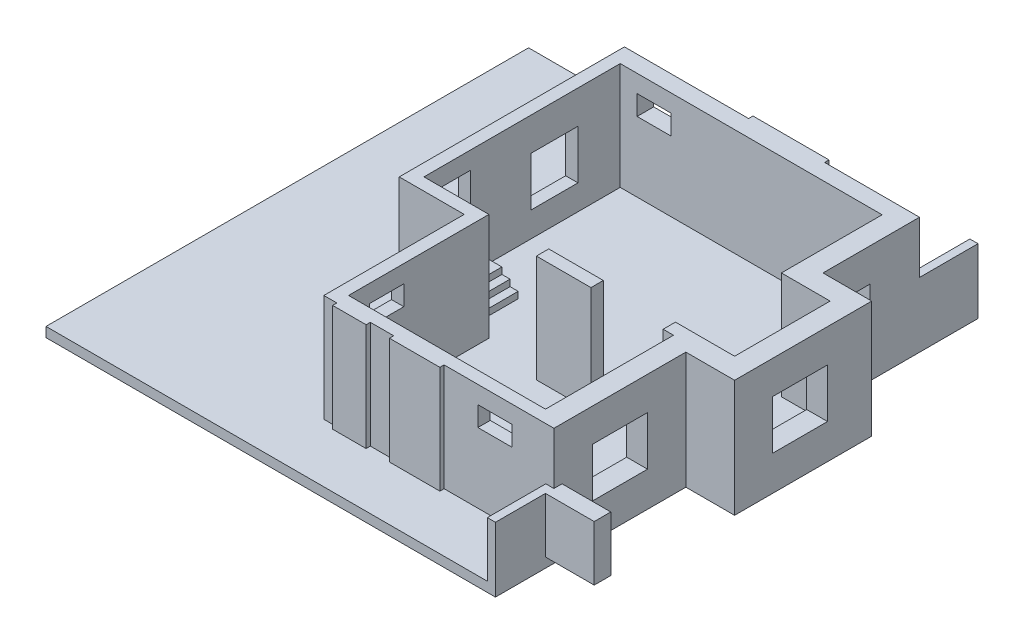
SolidWorks part; units mm, degrees
ref_plane "Спереди" through (0, 0, 0) normal (0, 0, 1) x (1, 0, 0)
ref_plane "Сверху" through (0, 0, 0) normal (0, 1, 0) x (1, 0, 0)
ref_plane "Справа" through (0, 0, 0) normal (1, 0, 0) x (0, 0, -1)
sketch "Эскиз2" plane through (0, 0, 0) normal (0, 1, 0) x (1, 0, 0)
  line L0 (0, 0) -> (-14310, 0) construction
  line L1 (0, 0) -> (0, -10805) construction
  line L2 (0, -3035) -> (-14310, -3035) construction
  line L3 (0, -6485) -> (-14310, -6485) construction
  line L4 (-1500, 0) -> (-1500, -10805) construction
  line L5 (-14310, 0) -> (-14310, -10805) construction
  line L6 (0, -10805) -> (-14310, -10805) construction
  dimension "D1" = 1500
  dimension "D2" = 12810
  dimension "D3" = 3035
  dimension "D4" = 3450
  dimension "D5" = 4320
sketch "Эскиз1" plane through (0, 0, 0) normal (0, 1, 0) x (1, 0, 0)
  line L0 (0, 0) -> (-14310, 0) construction
  line L1 (-1500, 0) -> (-1500, -10805) construction
  line L2 (0, -3035) -> (-14310, -3035) construction
  line L3 (0, 0) -> (0, -10805) construction
  line L4 (0, -6485) -> (-14310, -6485) construction
  line L5 (0, -10805) -> (-14310, -10805) construction
  line L6 (-7880, -6675) -> (-7880, -6295)
  line L7 (-10260, 255) -> (-6440, 255)
  line L8 (-6440, 255) -> (-6440, 390)
  line L9 (-6440, 390) -> (-4100, 390)
  line L10 (-4100, 390) -> (-4100, 255)
  line L11 (-4100, 255) -> (-1180, 255)
  line L12 (-1180, 255) -> (-1180, -2715)
  line L13 (-1180, -2715) -> (320, -2715)
  line L14 (320, -2715) -> (320, -6935)
  line L15 (320, -6935) -> (-1180, -6935)
  line L16 (-1180, -6935) -> (-1180, -10995)
  line L17 (-10260, 255) -> (-10260, -6675)
  line L18 (-10260, -6675) -> (-8260, -6675)
  line L19 (-8260, -6675) -> (-8260, -10995)
  line L20 (-1180, -10995) -> (-4560, -10995)
  line L21 (-4560, -10995) -> (-4560, -11125)
  line L22 (-4560, -11125) -> (-6110, -11125)
  line L23 (-6110, -11125) -> (-6110, -10995)
  line L24 (-6110, -10995) -> (-6830, -10995)
  line L25 (-6830, -10995) -> (-6830, -11125)
  line L26 (-6830, -11125) -> (-7860, -11125)
  line L27 (-7860, -11125) -> (-7860, -10995)
  line L28 (-7860, -10995) -> (-8260, -10995)
  line L29 (-9880, -255) -> (-1820, -255)
  line L30 (-1820, -255) -> (-1820, -3355)
  line L31 (-1820, -3355) -> (-320, -3355)
  line L32 (-320, -3355) -> (-320, -6295)
  line L33 (-320, -6295) -> (-2140, -6295)
  line L34 (-2140, -6295) -> (-2140, -6675)
  line L35 (-1820, -10615) -> (-7880, -10615)
  line L36 (-7880, -10615) -> (-7880, -6675)
  line L39 (-7880, -6295) -> (-9880, -6295)
  line L40 (-9880, -6295) -> (-9880, -255)
  line L41 (-2140, -6675) -> (-1820, -6675)
  line L42 (-6040, -6295) -> (-4360, -6295)
  line L43 (-6040, -6295) -> (-6040, -6675)
  line L44 (-6040, -6675) -> (-4360, -6675)
  line L45 (-4360, -6295) -> (-4360, -6675)
  line L46 (-1820, -6675) -> (-1820, -10615)
  dimension "D4" = 255
  dimension "D5" = 510
  dimension "D6" = 320
  dimension "D7" = 135
  dimension "D8" = 135
  dimension "D9" = 640
  dimension "D10" = 320
  dimension "D11" = 640
  dimension "D12" = 320
  dimension "D13" = 640
  dimension "D14" = 450
  dimension "D15" = 2340
  dimension "D16" = 3820
  dimension "D17" = 640
  dimension "D18" = 640
  dimension "D19" = 130
  dimension "D20" = 130
  dimension "D21" = 1550
  dimension "D22" = 720
  dimension "D23" = 1030
  dimension "D24" = 400
  dimension "D25" = 320
  dimension "D26" = 190
  dimension "D28" = 380
  dimension "D29" = 320
  dimension "D30" = 1680
  dimension "D31" = 2220
  dimension "D32" = 380
  dimension "D33" = 3380
  dimension "D34" = 190
  dimension "D35" = 9080
  dimension "D38" = 380
extrude "Бобышка-Вытянуть1" add sketch "Эскиз1" along normal blind 3300
sketch "Эскиз3" plane through (0, 0, 0) normal (0, 1, 0) x (1, 0, 0)
  line L0 (-1180, -6935) -> (-1180, -10995) construction
  line L1 (-1430, 2055) -> (-1180, 2055)
  line L2 (-1430, 2055) -> (-1430, 255)
  line L3 (-1430, 255) -> (-1180, 255)
  line L4 (-1180, 2055) -> (-1180, 255)
  line L5 (-1430, -10995) -> (-1180, -10995)
  line L6 (-1430, -10995) -> (-1430, -12795)
  line L7 (-1430, -12795) -> (-1180, -12795)
  line L8 (-1180, -10995) -> (-1180, -12795)
  line L9 (-1180, -10745) -> (320, -10745)
  line L10 (-1180, -10745) -> (-1180, -11255)
  line L11 (-1180, -11255) -> (320, -11255)
  line L12 (320, -10745) -> (320, -11255)
  dimension "D1" = 250
  dimension "D2" = 250
  dimension "D3" = 260
  dimension "D4" = 1500
  dimension "D5" = 1800
  dimension "D6" = 250
  dimension "D7" = 1800
extrude "Бобышка-Вытянуть2" add sketch "Эскиз3" along normal blind 1695 contours L8 L5 L6 L7 | L12 L9 L10 L8 L11 | L4 L3 L2 L1
sketch "Эскиз4" plane through (0, 0, 0) normal (0, 1, 0) x (1, 0, 0)
  line L0 (-1180, 2055) -> (-1180, -2715)
  line L1 (-15010, 2055) -> (-1180, 2055)
  line L2 (-15010, 2055) -> (-15010, -12795)
  line L3 (-15010, -12795) -> (-1180, -12795)
  line L4 (-1180, -2715) -> (320, -2715)
  line L5 (320, -2715) -> (320, -6935)
  line L6 (320, -6935) -> (-1180, -6935)
  line L7 (-1180, -6935) -> (-1180, -12795)
  line L9 (-14310, 0) -> (-14310, -10805) construction
  line L10 (0, 0) -> (-14310, 0) construction
  line L11 (0, -10805) -> (-14310, -10805) construction
  line L13 (-1500, 0) -> (-1500, -10805) construction
  line L14 (0, -6485) -> (-14310, -6485) construction
  line L15 (0, 0) -> (0, -10805) construction
  line L16 (0, -3035) -> (-14310, -3035) construction
  dimension "D1" = 700
  dimension "D2" = 2055
  dimension "D3" = 1990
  dimension "D4" = 320
  dimension "D5" = 450
  dimension "D6" = 320
  dimension "D7" = 320
  dimension "D8" = 320
extrude "Бобышка-Вытянуть3" add sketch "Эскиз4" against normal blind 300
sketch "Эскиз5" plane through (-9880, 0, 0) normal (1, 0, 0) x (0, 0, -1)
  line L0 (-6295, 3300) -> (-6295, 0) construction
  line L1 (-6165, 2760) -> (-4855, 2760)
  line L2 (-6165, 2760) -> (-6165, 660)
  line L3 (-6165, 660) -> (-4855, 660)
  line L4 (-4855, 2760) -> (-4855, 660)
  line L5 (-6295, 0) -> (-255, 0) construction
  line L6 (-255, 3300) -> (-255, 0) construction
  line L7 (-2995, 2280) -> (-1555, 2280)
  line L8 (-2995, 2280) -> (-2995, 770)
  line L9 (-2995, 770) -> (-1555, 770)
  line L10 (-1555, 2280) -> (-1555, 770)
  dimension "D1" = 1310
  dimension "D2" = 130
  dimension "D3" = 2100
  dimension "D4" = 2760
  dimension "D5" = 1300
  dimension "D6" = 1440
  dimension "D7" = 1510
  dimension "D8" = 2280
extrude "Вырез-Вытянуть1" cut sketch "Эскиз5" against normal up to next (380 mm away)
sketch "Эскиз6" plane through (0, 0, 0) normal (0, 1, 0) x (1, 0, 0)
  line L1 (-9880, -6295) -> (-8480, -6295)
  line L2 (-9880, -6295) -> (-9880, -4795)
  line L3 (-9880, -4795) -> (-8480, -4795)
  line L4 (-8480, -6295) -> (-8480, -4795)
  dimension "D1" = 1400
  dimension "D2" = 1500
extrude "Бобышка-Вытянуть4" add sketch "Эскиз6" along normal blind 200
sketch "Эскиз7" plane through (0, 200, 0) normal (0, 1, 0) x (1, 0, 0)
  line L0 (-8480, -4795) -> (-9880, -4795) construction
  line L1 (-9880, -6295) -> (-8730, -6295)
  line L2 (-9880, -6295) -> (-9880, -4795)
  line L3 (-9880, -4795) -> (-8730, -4795)
  line L4 (-8730, -6295) -> (-8730, -4795)
  dimension "D1" = 1150
extrude "Бобышка-Вытянуть5" add sketch "Эскиз7" along normal blind 200
sketch "Эскиз8" plane through (0, 400, 0) normal (0, 1, 0) x (1, 0, 0)
  line L0 (-8730, -4795) -> (-9880, -4795) construction
  line L1 (-9880, -6295) -> (-8980, -6295)
  line L2 (-9880, -6295) -> (-9880, -4795)
  line L3 (-9880, -4795) -> (-8980, -4795)
  line L4 (-8980, -6295) -> (-8980, -4795)
  dimension "D1" = 900
extrude "Бобышка-Вытянуть6" add sketch "Эскиз8" along normal blind 200
sketch "Эскиз9" plane through (-1820, 0, 0) normal (-1, 0, 0) x (0, 0, 1)
  line L0 (255, 3300) -> (255, 0) construction
  line L1 (1275, 2280) -> (2715, 2280)
  line L2 (1275, 2280) -> (1275, 770)
  line L3 (1275, 770) -> (2715, 770)
  line L4 (2715, 2280) -> (2715, 770)
  line L5 (255, 0) -> (3355, 0) construction
  dimension "D1" = 1440
  dimension "D2" = 1020
  dimension "D3" = 2280
  dimension "D4" = 1510
extrude "Вырез-Вытянуть2" cut sketch "Эскиз9" against normal up to next (640 mm away)
sketch "Эскиз10" plane through (-1820, 0, 0) normal (-1, 0, 0) x (0, 0, 1)
  line L0 (10615, 3300) -> (10615, 0) construction
  line L1 (8115, 2280) -> (9815, 2280)
  line L2 (8115, 2280) -> (8115, 770)
  line L3 (8115, 770) -> (9815, 770)
  line L4 (9815, 2280) -> (9815, 770)
  line L5 (6675, 0) -> (10615, 0) construction
  dimension "D1" = 1700
  dimension "D2" = 800
  dimension "D3" = 2280
  dimension "D4" = 1510
extrude "Вырез-Вытянуть3" cut sketch "Эскиз10" against normal up to next (640 mm away)
sketch "Эскиз11" plane through (0, 0, 255) normal (0, 0, 1) x (1, 0, 0)
  line L0 (-9880, 3300) -> (-9880, 0) construction
  line L1 (-9360, 2760) -> (-8310, 2760)
  line L2 (-9360, 2760) -> (-9360, 2150)
  line L3 (-9360, 2150) -> (-8310, 2150)
  line L4 (-8310, 2760) -> (-8310, 2150)
  line L5 (-9880, 0) -> (-1820, 0) construction
  dimension "D1" = 1050
  dimension "D2" = 520
  dimension "D3" = 2760
  dimension "D4" = 610
extrude "Вырез-Вытянуть4" cut sketch "Эскиз11" against normal up to next (510 mm away)
sketch "Эскиз12" plane through (-7880, 0, 0) normal (1, 0, 0) x (0, 0, -1)
  line L0 (-10615, 3300) -> (-10615, 0) construction
  line L1 (-9965, 2760) -> (-8915, 2760)
  line L2 (-9965, 2760) -> (-9965, 2150)
  line L3 (-9965, 2150) -> (-8915, 2150)
  line L4 (-8915, 2760) -> (-8915, 2150)
  line L5 (-10615, 0) -> (-6295, 0) construction
  dimension "D1" = 650
  dimension "D2" = 1050
  dimension "D3" = 2760
  dimension "D4" = 610
extrude "Вырез-Вытянуть5" cut sketch "Эскиз12" against normal up to next (380 mm away)
sketch "Эскиз13" plane through (0, 0, 10615) normal (0, 0, -1) x (-1, 0, 0)
  line L0 (1820, 3300) -> (1820, 0) construction
  line L1 (2470, 2760) -> (3520, 2760)
  line L2 (2470, 2760) -> (2470, 2150)
  line L3 (2470, 2150) -> (3520, 2150)
  line L4 (3520, 2760) -> (3520, 2150)
  line L5 (1820, 0) -> (7880, 0) construction
  dimension "D1" = 650
  dimension "D2" = 1050
  dimension "D3" = 610
  dimension "D4" = 2760
extrude "Вырез-Вытянуть6" cut sketch "Эскиз13" against normal up to next (380 mm away)
sketch "Эскиз14" plane through (-320, 0, 0) normal (-1, 0, 0) x (0, 0, 1)
  line L0 (3355, 3300) -> (3355, 0) construction
  line L1 (4075, 2280) -> (5775, 2280)
  line L2 (4075, 2280) -> (4075, 770)
  line L3 (4075, 770) -> (5775, 770)
  line L4 (5775, 2280) -> (5775, 770)
  line L5 (3355, 0) -> (6295, 0) construction
  dimension "D1" = 1700
  dimension "D2" = 720
  dimension "D3" = 2280
  dimension "D4" = 1510
extrude "Вырез-Вытянуть7" cut sketch "Эскиз14" against normal up to next (640 mm away)
sketch "Эскиз15" plane through (0, 0, 0) normal (0, 1, 0) x (1, 0, 0)
  line L0 (-7192.8518, -10365) -> (-6796.2068, -10365) construction
  line L1 (-1500, 0) -> (-1500, -10805) construction
  line L2 (0, -10805) -> (-14310, -10805) construction
  line L4 (-7680, -9964.91) -> (-7680, -8245.09) construction
  line L5 (-1820, -10615) -> (-7880, -10615) construction
  line L6 (-5850, -10365) -> (-5850, -10325.2435) construction
  line L7 (-5500, -10365) -> (-5500, -10325.2435) construction
  line L8 (-2850, -10365) -> (-2850, -10343.6709) construction
  line L9 (-2500, -10365) -> (-2500, -10343.6709) construction
  line L11 (-7880, -10615) -> (-7880, -6295) construction
  line L12 (-7761.1747, -9605) -> (-7537.9024, -9605) construction
  line L13 (-7761.1747, -9355) -> (-7537.9024, -9355) construction
  line L14 (-7761.1747, -9105) -> (-7598.8253, -9105) construction
  circle A0 centre (-7680, -9355) radius 54
  circle A1 centre (-7680, -9605) radius 38
  circle A3 centre (-5850, -10365) radius 136.5
  circle A4 centre (-5500, -10365) radius 136.5
  circle A5 centre (-2850, -10365) radius 109.5
  circle A6 centre (-2500, -10365) radius 109.5
  circle A7 centre (-7680, -9105) radius 54
  dimension "D4" = 76
  dimension "D8" = 273
  dimension "D9" = 273
  dimension "D10" = 219
  dimension "D11" = 219
  dimension "D20" = 108
  dimension "D21" = 108
  dimension "D3" = 1000
  dimension "D5" = 4000
  dimension "D6" = 1200
  dimension "D7" = 250
  dimension "D13" = 350
  dimension "D15" = 350
  dimension "D16" = 200
  dimension "D18" = 250
  dimension "D19" = 250
extrude "Вырез-Вытянуть8" cut sketch "Эскиз15" against normal up to next (300 mm away)
